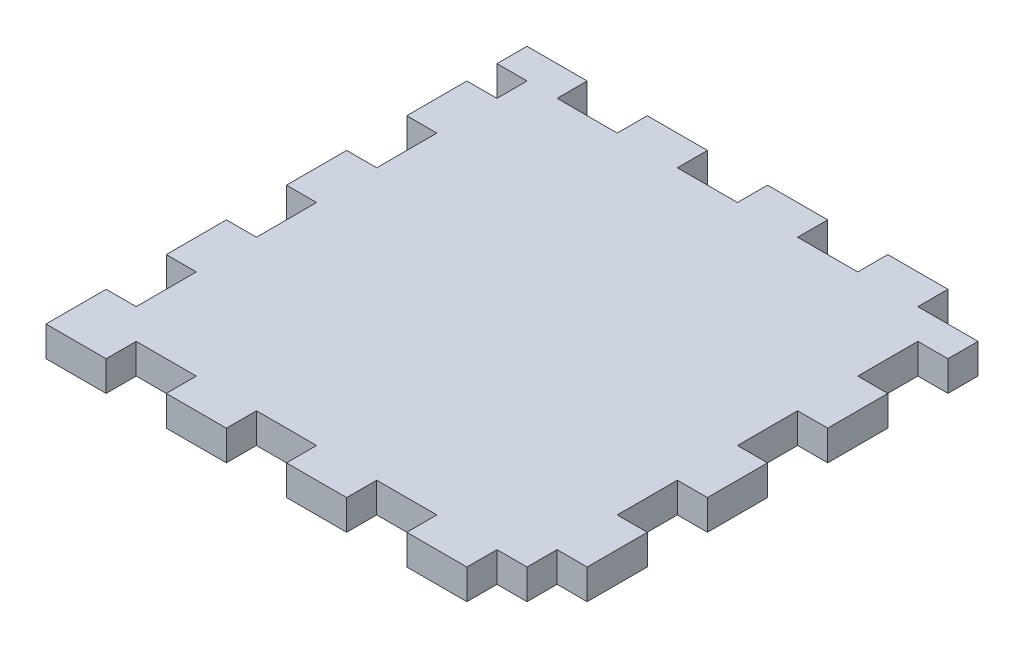
SolidWorks part; units mm, degrees
material "Acrylic (Medium-high impact)"
ref_plane "Front Plane" through (0, 0, 0) normal (0, 0, 1) x (1, 0, 0)
ref_plane "Top Plane" through (0, 0, 0) normal (0, 1, 0) x (1, 0, 0)
ref_plane "Right Plane" through (0, 0, 0) normal (1, 0, 0) x (0, 0, -1)
sketch "Sketch1" plane through (0, 0, 0) normal (0, 1, 0) x (1, 0, 0)
  line L1 (0, 0) -> (101.6, 0)
  line L2 (0, 0) -> (0, 101.6)
  line L3 (0, 101.6) -> (101.6, 101.6)
  line L4 (101.6, 0) -> (101.6, 101.6)
  dimension "D1" = 101.6
  dimension "D2" = 101.6
extrude "Boss-Extrude1" add sketch "Sketch1" along normal blind 6.35
ref_plane "Plane1" through (0, 0, -50.8) normal (0, 0, -1) x (-1, 0, 0)
ref_plane "Plane2" through (50.8, 0, 0) normal (-1, 0, 0) x (0, 0, 1)
sketch "Sketch2" plane through (0, 6.35, 0) normal (0, 1, 0) x (1, 0, 0)
  line L0 (6.35, 101.6) -> (6.35, 0)
  line L1 (101.6, 101.6) -> (0, 101.6) construction
  line L2 (0, 0) -> (101.6, 0) construction
  line L3 (0, 95.25) -> (101.6, 95.25)
  line L4 (0, 101.6) -> (0, 0) construction
  line L5 (101.6, 0) -> (101.6, 101.6) construction
  line L6 (12.7, 101.6) -> (12.7, 95.25)
  line L7 (0, 12.7) -> (6.35, 12.7)
  line L8 (0, 25.4) -> (6.35, 25.4)
  line L9 (0, 38.1) -> (6.35, 38.1)
  line L10 (0, 50.8) -> (6.35, 50.8)
  line L11 (0, 63.5) -> (6.35, 63.5)
  line L12 (0, 76.2) -> (6.35, 76.2)
  line L13 (0, 88.9) -> (6.35, 88.9)
  line L14 (0, 101.6) -> (6.35, 101.6)
  line L15 (25.4, 101.6) -> (25.4, 95.25)
  line L16 (38.1, 101.6) -> (38.1, 95.25)
  line L17 (50.8, 101.6) -> (50.8, 95.25)
  line L18 (63.5, 101.6) -> (63.5, 95.25)
  line L19 (76.2, 101.6) -> (76.2, 95.25)
  line L20 (88.9, 101.6) -> (88.9, 95.25)
  line L21 (101.6, 101.6) -> (101.6, 95.25)
  line L22 (95.25, 101.6) -> (95.25, 0)
  line L23 (95.25, 12.7) -> (101.6, 12.7)
  line L24 (95.25, 25.4) -> (101.6, 25.4)
  line L25 (95.25, 38.1) -> (101.6, 38.1)
  line L26 (0, 101.6) -> (0, 0)
  line L27 (0, 0) -> (101.6, 0)
  line L28 (101.6, 0) -> (101.6, 101.6)
  line L29 (101.6, 101.6) -> (0, 101.6)
  line L30 (0, 101.6) -> (0, 0)
  line L31 (0, 0) -> (101.6, 0)
  line L32 (101.6, 0) -> (101.6, 101.6)
  line L33 (101.6, 101.6) -> (0, 101.6)
  line L34 (95.25, 50.8) -> (101.6, 50.8)
  line L35 (95.25, 63.5) -> (101.6, 63.5)
  line L36 (95.25, 76.2) -> (101.6, 76.2)
  line L37 (95.25, 88.9) -> (101.6, 88.9)
  line L38 (95.25, 101.6) -> (101.6, 101.6)
  line L39 (0, 6.35) -> (101.6, 6.35)
  line L40 (12.7, 6.35) -> (12.7, 0)
  line L41 (25.4, 6.35) -> (25.4, 0)
  line L42 (38.1, 6.35) -> (38.1, 0)
  line L43 (50.8, 6.35) -> (50.8, 0)
  line L44 (63.5, 6.35) -> (63.5, 0)
  line L45 (76.2, 6.35) -> (76.2, 0)
  line L46 (88.9, 6.35) -> (88.9, 0)
  line L47 (101.6, 6.35) -> (101.6, 0)
  line M5 (0, 101.6) -> (0, 0)
  line M6 (0, 0) -> (101.6, 0)
  line M7 (101.6, 0) -> (101.6, 101.6)
  line M8 (101.6, 101.6) -> (0, 101.6)
  dimension "D1" = 6.35
  dimension "D2" = 6.35
  dimension "D3" = 12.7
  dimension "D4" = 12.7
  dimension "D7" = 6.35
  dimension "D8" = 12.7
  dimension "D10" = 6.35
  dimension "D11" = 12.7
  dimension "D6" = 0
  dimension "D5" = 8
  dimension "D9" = 8
extrude "Cut-Extrude1" cut sketch "Sketch2" against normal blind 6.35 contours L13 L0 L3 M5 | L12 L11 L0 M5 | L10 L9 L0 M5 | L8 L7 L0 M5 | L15 L6 L3 M8 | L17 L16 L3 M8 | L19 L18 L3 M8 | L22 L20 L3 M8 | L22 L3 M8 M7 | L37 L22 L36 L32 | L35 L22 L34 L32 | L25 L22 L24 M7 | L22 L39 L32 L23 | L39 L22 M6 M7 | L39 L46 L31 L22 | L45 L39 L44 L31 | L43 L39 L42 L31 | L41 L39 L40 L31
equation "\"acrillic thick\"= 0.25"
equation "\"D1@Boss-Extrude1\"=\"acrillic thick\""
equation "\"D1@Sketch2\"=\"acrillic thick\""
equation "\"D2@Sketch2\"=\"acrillic thick\""
equation "\"D7@Sketch2\"=\"acrillic thick\""
equation "\"D10@Sketch2\"=\"acrillic thick\""
